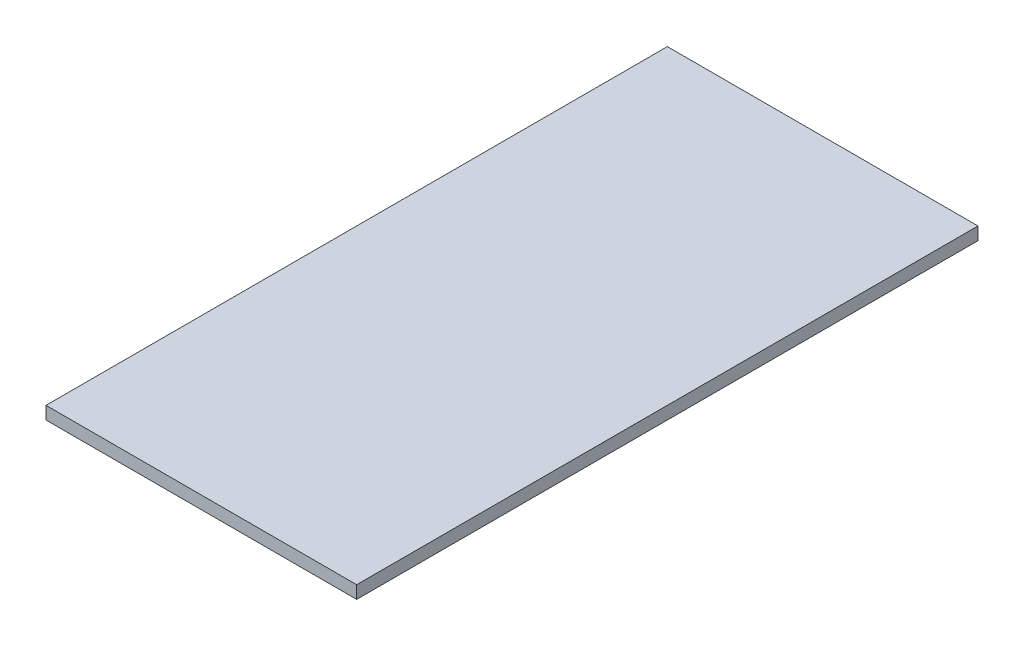
SolidWorks part; units mm, degrees
ref_plane "Front Plane" through (0, 0, 0) normal (0, 0, 1) x (1, 0, 0)
ref_plane "Top Plane" through (0, 0, 0) normal (0, 1, 0) x (1, 0, 0)
ref_plane "Right Plane" through (0, 0, 0) normal (1, 0, 0) x (0, 0, -1)
sketch "Sketch1" plane through (0, 0, 0) normal (0, 1, 0) x (1, 0, 0)
  line L1 (1219.2, -2438.4) -> (-1219.2, -2438.4)
  line L2 (1219.2, -2438.4) -> (1219.2, 2438.4)
  line L3 (1219.2, 2438.4) -> (-1219.2, 2438.4)
  line L4 (-1219.2, -2438.4) -> (-1219.2, 2438.4)
  line L5 (1219.2, -2438.4) -> (-1219.2, 2438.4) construction
  line L6 (1219.2, 2438.4) -> (-1219.2, -2438.4) construction
  point P0 (0, 0)
  dimension "D1" = 4876.8
  dimension "D2" = 2438.4
extrude "Boss-Extrude1" add sketch "Sketch1" along normal blind 100
sketch "Sketch2" plane through (0, 100, 0) normal (0, 1, 0) x (1, 0, 0)
  line L0 (-1219.2, 2438.4) -> (-1219.2, -2438.4) construction
  line L1 (-919.2, -2338.4) -> (-1169.2, -2338.4)
  line L2 (-919.2, -2338.4) -> (-919.2, -2228.4)
  line L3 (-919.2, -2088.4) -> (-1169.2, -2088.4)
  line L4 (-1169.2, -2338.4) -> (-1169.2, -2088.4)
  line L5 (-919.2, -2338.4) -> (-1169.2, -2088.4) construction
  line L6 (-919.2, -2088.4) -> (-1169.2, -2338.4) construction
  line L7 (-1219.2, -2438.4) -> (1219.2, -2438.4) construction
  line L8 (-919.2, -2228.4) -> (-519.2, -2228.4)
  line L9 (-919.2, -2213.4) -> (-874.2776, -2213.4) construction
  line L10 (-919.2, -2198.4) -> (-519.2, -2198.4)
  line L11 (-919.2, -2198.4) -> (-919.2, -2088.4)
  line L12 (518.6973, -2271.9533) -> (948.6973, -2271.9533)
  line L13 (518.6973, -2241.9533) -> (918.6973, -2241.9533)
  line L14 (918.6973, -2241.9533) -> (918.6973, -1841.9533)
  line L15 (948.6973, -2271.9533) -> (948.6973, -1841.9533)
  line L17 (518.6973, -1539.0748) -> (218.6973, -1539.0748)
  line L18 (218.6973, -1539.0748) -> (218.6973, -1567.2032)
  line L19 (218.6973, -1567.2032) -> (518.6973, -1567.2032)
  line L20 (-1019.2, -1938.4) -> (-719.2, -1938.4)
  line L21 (-719.2, -1938.4) -> (-719.2, -1908.4)
  line L22 (-719.2, -1908.4) -> (-989.2, -1908.4)
  line L23 (-989.2, -1908.4) -> (-989.2, -415)
  line L24 (-989.2, -415) -> (-679.8558, -415)
  line L25 (100, -400) -> (-1082.2018, -400) construction
  line L26 (-1019.2, -1938.4) -> (-1019.2, -385)
  line L27 (-1019.2, -385) -> (-679.8558, -385)
  line L28 (100, -400) -> (100, -1150) construction
  line L29 (100, -400) -> (630.3301, -930.3301) construction
  line L30 (619.6179, -940.8301) -> (100, -421.2121)
  line L31 (100, -400) -> (-430.3301, 130.3301) construction
  line L32 (640.8301, -919.6179) -> (121.2121, -400)
  line L33 (100, -400) -> (630.3301, 130.3301) construction
  line L34 (630.3301, 130.3301) -> (-430.3301, -930.3301) construction
  line L35 (-440.8301, -919.6179) -> (78.7879, -400)
  line L36 (640.8301, 119.6179) -> (121.2121, -400)
  line L37 (100, -378.7879) -> (619.6179, 140.8301)
  line L38 (78.7879, -400) -> (-440.8301, 119.6179)
  line L39 (100, -421.2121) -> (-419.6179, -940.8301)
  line L40 (100, -378.7879) -> (-419.6179, 140.8301)
  line L41 (100, -400) -> (100, 350) construction
  line L42 (100, 350) -> (100, 632.1211) construction
  line L43 (85, 379.8558) -> (85, 679.8558)
  line L44 (115, 379.8558) -> (115, 679.8558)
  line L45 (85, 679.8558) -> (115, 679.8558)
  line L47 (83.4854, 707.2433) -> (113.3638, 709.8558)
  line L48 (76.8899, 753.4856) -> (106.3073, 759.3304)
  line L49 (70.3336, 781.5256) -> (99.2927, 789.3304)
  line L50 (55.7416, 825.8982) -> (83.6807, 836.8045)
  line L51 (43.6288, 853.9382) -> (70.7213, 866.8045)
  line L52 (21.3238, 894.9789) -> (46.8572, 910.7139)
  line L53 (2.4819, 923.0189) -> (26.6982, 940.7139)
  line L54 (-27.0883, 959.1776) -> (-4.9389, 979.4001)
  line L55 (-55.1742, 987.2176) -> (-34.988, 1009.4001)
  line L56 (-91.1552, 1016.5642) -> (-73.7258, 1040.9739)
  line L57 (-96.6307, 1058.6167) -> (-115.8169, 1035.5623)
  line L58 (-130.3938, 1090.3604) -> (-152.2226, 1069.7905)
  line L59 (-147.2459, 1109.4797) -> (-170.3937, 1090.4064)
  line L60 (-199.78, 1130.8217) -> (-174.4991, 1146.9613)
  line L61 (-188.5451, 1170.8217) -> (-214.9254, 1156.5496)
  line L62 (-208.0915, 1212.8401) -> (-236.0018, 1201.8568)
  line L63 (-245.209, 1227.7495) -> (-216.6304, 1236.8532)
  line L64 (-257.4693, 1276.1916) -> (-228.0007, 1281.779)
  line L65 (-231.9131, 1306.9631) -> (-261.6879, 1303.3468)
  line L66 (-264.7021, 1353.1649) -> (-264.7021, 1553.1649)
  line L67 (-264.7021, 1553.1649) -> (-234.7085, 1553.1649)
  line L68 (-234.7085, 1553.1649) -> (-234.7085, 1353.1649)
  arc A0 (-519.2, -2228.4) -> (-256.4254, -2117.5698) centre (-519.2, -1861.47) ccw
  arc A1 (-519.2, -2198.4) -> (-277.9097, -2096.6312) centre (-519.2, -1861.47) ccw
  arc A3 (208.9279, -2130.8016) -> (-256.4254, -2117.5698) centre (-29.8396, -2338.4) ccw
  arc A4 (231.5673, -2111.1176) -> (518.6973, -2241.9533) centre (518.6973, -1861.47) ccw
  arc A5 (208.9279, -2130.8016) -> (518.6973, -2271.9533) centre (518.6973, -1861.47) ccw
  arc A6 (231.5673, -2111.1176) -> (-277.9097, -2096.6312) centre (-29.8396, -2338.4) ccw
  arc A7 (918.6973, -1841.9533) -> (518.6973, -1567.2032) centre (518.6973, -1995.7519) ccw
  arc A8 (948.6973, -1841.9533) -> (518.6973, -1539.0748) centre (518.6973, -1995.7519) ccw
  arc A9 (640.8301, -919.6179) -> (640.8301, 119.6179) centre (100, -400) ccw
  arc A10 (-679.8558, -415) -> (115, 379.8558) centre (100, -400) ccw
  arc A11 (-440.8301, 119.6179) -> (-440.8301, -919.6179) centre (100, -400) ccw
  arc A12 (-419.6179, -940.8301) -> (619.6179, -940.8301) centre (100, -400) ccw
  arc A13 (619.6179, 140.8301) -> (-419.6179, 140.8301) centre (100, -400) ccw
  arc A14 (85, 379.8558) -> (-679.8558, -385) centre (100, -400) ccw
  arc A17 (-264.7021, 1353.1649) -> (-261.6879, 1303.3468) centre (148.4961, 1353.1649) ccw
  arc A18 (-234.7085, 1353.1649) -> (-231.9131, 1306.9631) centre (148.4961, 1353.1649) ccw
  arc A19 (70.3336, 781.5256) -> (55.7416, 825.8982) centre (-343.9653, 669.8681) ccw
  arc A20 (83.4854, 707.2433) -> (76.8899, 753.4856) centre (-343.9653, 669.8681) ccw
  arc A21 (113.3638, 709.8558) -> (106.3073, 759.3304) centre (-343.9653, 669.8681) ccw
  arc A22 (99.2927, 789.3304) -> (83.6807, 836.8045) centre (-343.9653, 669.8681) ccw
  arc A23 (70.7213, 866.8045) -> (46.8572, 910.7139) centre (-343.9653, 669.8681) ccw
  arc A24 (43.6288, 853.9382) -> (21.3238, 894.9789) centre (-343.9653, 669.8681) ccw
  arc A25 (26.6982, 940.7139) -> (-4.9389, 979.4001) centre (-343.9653, 669.8681) ccw
  arc A26 (2.4819, 923.0189) -> (-27.0883, 959.1776) centre (-343.9653, 669.8681) ccw
  arc A27 (-55.1742, 987.2176) -> (-95.0137, 1019.345) centre (-343.9653, 669.8681) ccw
  arc A28 (-34.988, 1009.4001) -> (-73.7258, 1040.9739) centre (-343.9653, 669.8681) ccw
  arc A29 (-152.2226, 1069.7905) -> (-115.8169, 1035.5623) centre (148.4961, 1353.1649) ccw
  arc A30 (-130.3938, 1090.3604) -> (-96.6307, 1058.6167) centre (148.4961, 1353.1649) ccw
  arc A31 (-174.4991, 1146.9613) -> (-147.2459, 1109.4797) centre (148.4961, 1353.1649) ccw
  arc A32 (-199.78, 1130.8217) -> (-170.3937, 1090.4064) centre (148.4961, 1353.1649) ccw
  arc A33 (-208.0915, 1212.8401) -> (-188.5451, 1170.8217) centre (148.4961, 1353.1649) ccw
  arc A34 (-236.0018, 1201.8568) -> (-214.9254, 1156.5496) centre (148.4961, 1353.1649) ccw
  arc A35 (-228.0007, 1281.779) -> (-216.6304, 1236.8532) centre (148.4961, 1353.1649) ccw
  arc A36 (-257.4693, 1276.1916) -> (-245.209, 1227.7495) centre (148.4961, 1353.1649) ccw
  point P0 (-1044.2, -2213.4)
  point P9 (-1044.2, -2338.4)
  point P95 (-82.4405, 1028.7691)
  dimension "D9" = 673.8601
  dimension "D10" = 733.8601
  dimension "D11" = 632.794
  dimension "D12" = 489.3604
  dimension "D13" = 760.9667
  dimension "D15" = 30
  dimension "D21" = 857.0975
  dimension "D28" = 1500
  dimension "D31" = 1560
  dimension "D1" = 250
  dimension "D2" = 250
  dimension "D3" = 50
  dimension "D4" = 100
  dimension "D5" = 400
  dimension "D6" = 15
  dimension "D7" = 15
  dimension "D8" = 125
  dimension "D14" = 1037.8973
  dimension "D16" = 30
  dimension "D17" = 30
  dimension "D18" = 400
  dimension "D19" = 430
  dimension "D20" = 400
  dimension "D22" = 400
  dimension "D23" = 300
  dimension "D24" = 300
  dimension "D25" = 270
  dimension "D26" = 30
  dimension "D27" = 150
  dimension "D29" = 100
  dimension "D30" = 400
  dimension "D32" = 15
  dimension "D33" = 15
  dimension "D34" = 100
  dimension "D35" = 45
  dimension "D36" = 15
  dimension "D37" = 45
  dimension "D38" = 15
  dimension "D39" = 15
  dimension "D40" = 15
  dimension "D41" = 1499.7
  dimension "D42" = 519.6179
  dimension "D43" = 45
  dimension "D44" = 15
  dimension "D45" = 15
  dimension "D46" = 15
  dimension "D47" = 15
  dimension "D48" = 1499.7
  dimension "D49" = 15
  dimension "D50" = 15
  dimension "D51" = 300
  dimension "D52" = 30
  dimension "D53" = 50
  dimension "D54" = 30
  dimension "D55" = 50
  dimension "D56" = 30
  dimension "D57" = 50
  dimension "D58" = 30
  dimension "D59" = 50
  dimension "D60" = 30
  dimension "D61" = 50
  dimension "D62" = 30
  dimension "D63" = 50
  dimension "D64" = 40
  dimension "D65" = 50
  dimension "D66" = 40
  dimension "D67" = 50
  dimension "D68" = 40
  dimension "D69" = 50
  dimension "D70" = 40
  dimension "D71" = 200
  dimension "D72" = 29.9936
  dimension "D73" = 842.2664
  dimension "D74" = 428.9653
